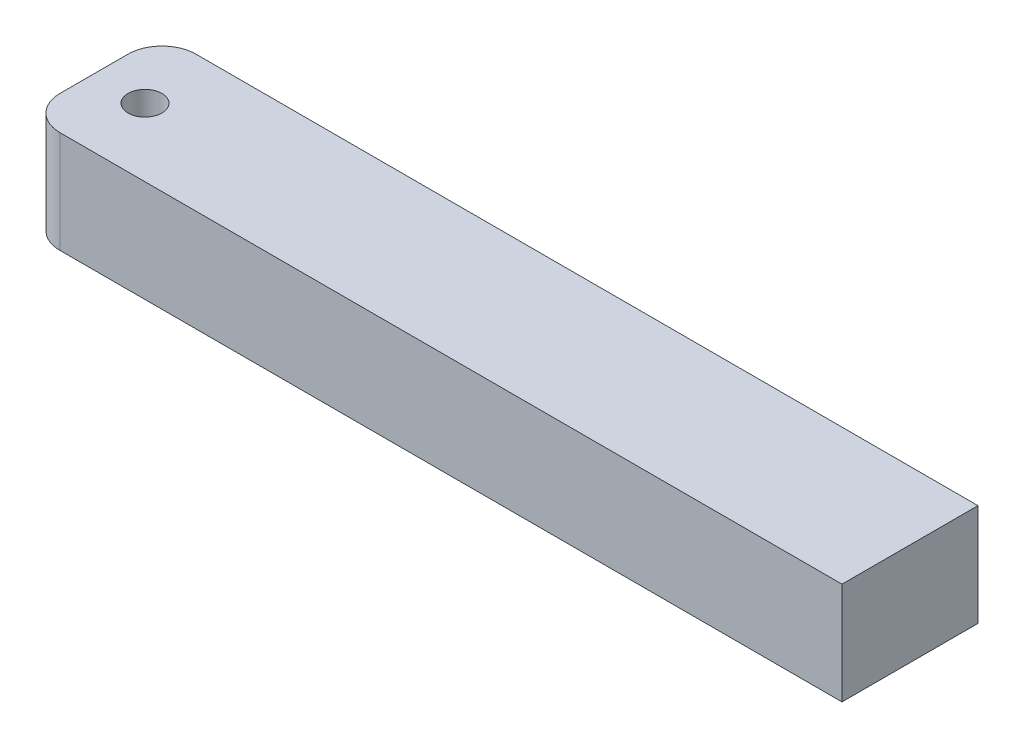
SolidWorks part; units mm, degrees
ref_plane "Front Plane" through (0, 0, 0) normal (0, 0, 1) x (1, 0, 0)
ref_plane "Top Plane" through (0, 0, 0) normal (0, 1, 0) x (1, 0, 0)
ref_plane "Right Plane" through (0, 0, 0) normal (1, 0, 0) x (0, 0, -1)
sketch "Sketch1" plane through (0, 0, 0) normal (0, 1, 0) x (1, 0, 0)
  line L1 (0, 0) -> (-292.1, 0)
  line L2 (0, 0) -> (0, 50.8)
  line L3 (0, 50.8) -> (-292.1, 50.8)
  line L4 (-304.8, 12.7) -> (-304.8, 38.1)
  arc A0 (-304.8, 12.7) -> (-292.1, 0) centre (-292.1, 12.7) ccw
  arc A1 (-304.8, 38.1) -> (-292.1, 50.8) centre (-292.1, 38.1) cw
  circle A2 centre (-285.75, 25.4) radius 6.35
  dimension "D1" = 12.7
  dimension "D3" = 12.7
  dimension "D2" = 25.4
  dimension "D4" = 19.05
  dimension "D5" = 304.8
extrude "Boss-Extrude1" add sketch "Sketch1" along normal blind 38.1
